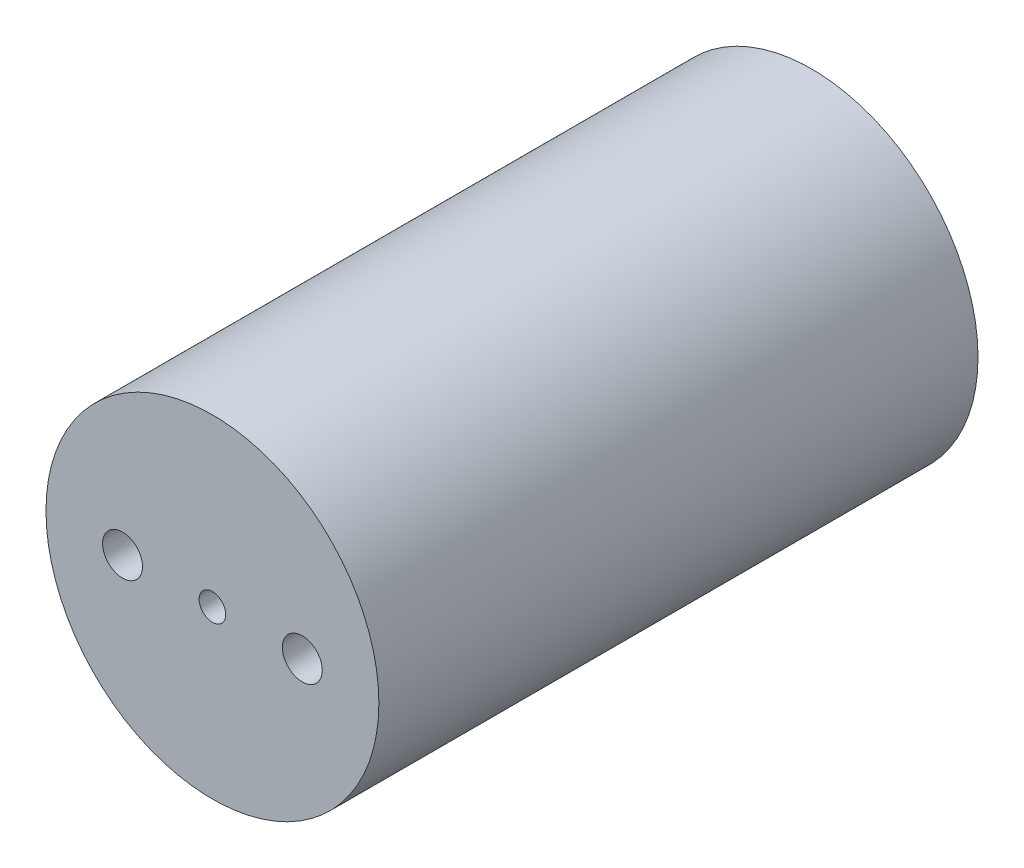
SolidWorks part; units mm, degrees
ref_plane "Front Plane" through (0, 0, 0) normal (0, 0, 1) x (1, 0, 0)
ref_plane "Top Plane" through (0, 0, 0) normal (0, 1, 0) x (1, 0, 0)
ref_plane "Right Plane" through (0, 0, 0) normal (1, 0, 0) x (0, 0, -1)
sketch "Sketch1" plane through (0, 0, 0) normal (0, 0, 1) x (1, 0, 0)
  circle A0 centre (0, 0) radius 50
  circle A1 centre (0, 0) radius 4
  dimension "D1" = 100
  dimension "D2" = 8
extrude "Boss-Extrude1" add sketch "Sketch1" along normal blind 180
sketch "Sketch2" plane through (0, 0, 180) normal (0, 0, 1) x (1, 0, 0)
  line L0 (0, 27) -> (0, 38.7765) construction
  circle A0 centre (0, 0) radius 27 construction
  circle A1 centre (27, 0) radius 6
  circle A2 centre (-27, 0) radius 6
  dimension "D1" = 54
  dimension "D2" = 12
extrude "Cut-Extrude1" cut sketch "Sketch2" against normal through all
